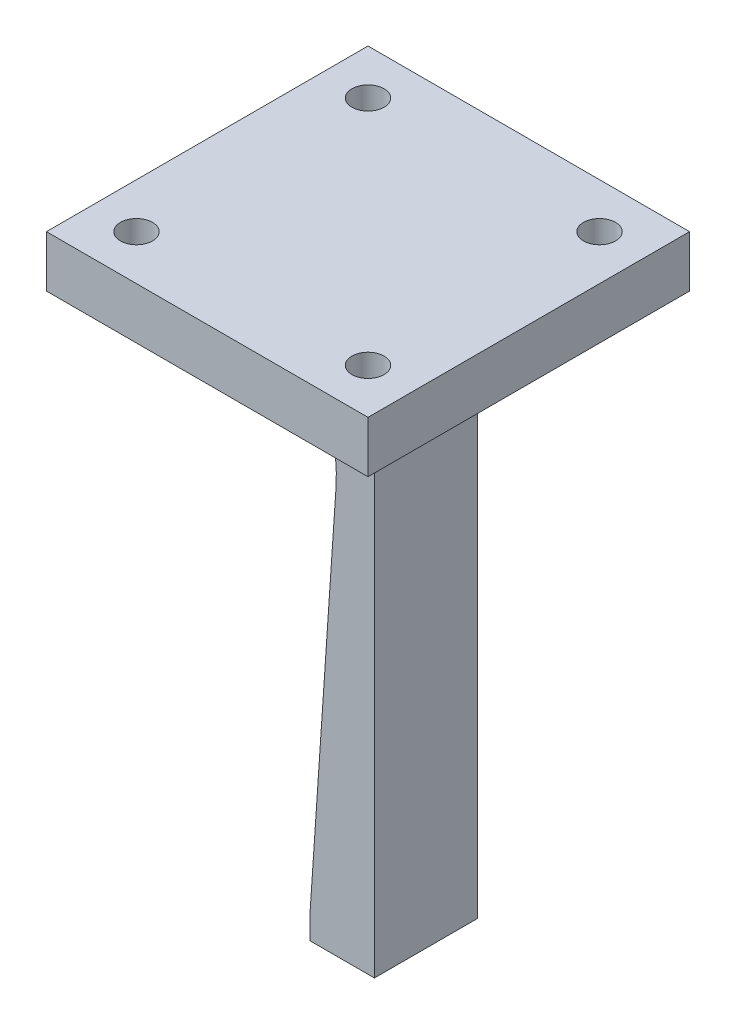
SolidWorks part; units mm, degrees
material "PBT Общее назначение"
ref_plane "Спереди" through (0, 0, 0) normal (0, 0, 1) x (1, 0, 0)
ref_plane "Сверху" through (0, 0, 0) normal (0, 1, 0) x (1, 0, 0)
ref_plane "Справа" through (0, 0, 0) normal (1, 0, 0) x (0, 0, -1)
sketch "Эскиз1" plane through (0, 0, 0) normal (0, 1, 0) x (1, 0, 0)
  line L0 (0, 0) -> (13, 0)
  line L1 (0, 0) -> (0, 13)
  line L2 (13, 0) -> (13, 13)
  line L3 (0, 13) -> (13, 13)
  line L4 (-6, 19) -> (19, 19)
  line L5 (-6, 19) -> (-6, -6)
  line L6 (19, 19) -> (19, -6)
  line L7 (-6, -6) -> (19, -6)
  line L8 (6.5, 19) -> (6.5, -6) construction
  line L9 (19, 6.5) -> (-6, 6.5) construction
  line L10 (6.5, 13) -> (6.5, 0) construction
  line L11 (13, 6.5) -> (0, 6.5) construction
  dimension "D1" = 13
  dimension "D2" = 13
  dimension "D3" = 25
  dimension "D4" = 25
extrude "Бобышка-Вытянуть1" add sketch "Эскиз1" along normal blind 4
sketch "Эскиз5" plane through (0, 4, 0) normal (0, 1, 0) x (1, 0, 0)
  line L0 (19, 6.5) -> (-6, 6.5) construction
  line L1 (19, -6) -> (19, 19) construction
  line L2 (-6, 19) -> (-6, -6) construction
ref_plane "Плоскость1" through (0, 0, -6.5) normal (0, 0, -1) x (-1, 0, 0)
sketch "Эскиз6" plane through (0, 0, -6.5) normal (0, 0, -1) x (-1, 0, 0)
  line L0 (-13, 4) -> (-13, 0) construction
  line L1 (-13, 4) -> (-13, 0) construction
  line L2 (-13, 4) -> (-9, 4)
  line L3 (-9, 4) -> (-9, -40)
  line L4 (-9, -40) -> (-6, -40)
  line L5 (-6, -40) -> (-6, -42)
  line L6 (-6, -42) -> (-11, -42)
  line L7 (-11, -42) -> (-11, 2)
  line L8 (-11, 2) -> (-13, 2)
  line L9 (-13, 2) -> (-13, 4)
  dimension "D1" = 2
  dimension "D2" = 2
  dimension "D3" = 2
  dimension "D4" = 5
  dimension "D5" = 42
  dimension "D6" = 2
extrude "Бобышка-Вытянуть5" add sketch "Эскиз6" along normal blind 4 and the other way blind 4
sketch "Эскиз7" plane through (0, 0, -10.5) normal (0, 0, -1) x (-1, 0, 0)
  line L0 (-9, -40) -> (-9, 4) construction
  line L1 (-6, -40) -> (-9, -40) construction
  line L2 (-9, -40) -> (-9, 4)
  line L3 (-6, -40) -> (-9, -40)
  line L4 (-6, -40) -> (-9, 4)
extrude "Бобышка-Вытянуть6" add sketch "Эскиз7" against normal up to surface (8 mm away) up to face at (9.75, -19, -2.5)
sketch "Эскиз9" plane through (0, 0, -2.5) normal (0, 0, 1) x (1, 0, 0)
  line L0 (9, 4) -> (0, 4)
  line L1 (0, 4) -> (0, 2)
  line L2 (6, -40) -> (9, 4) construction
  line L3 (8.0095, -10.527) -> (9, 4)
  arc A0 (8.0095, -10.527) -> (0, 2) centre (-4.4615, -9.6767) ccw
  dimension "D2" = 25
  dimension "D1" = 2
extrude "Бобышка-Вытянуть7" add sketch "Эскиз9" against normal blind 8
sketch "Эскиз10" plane through (0, 4, 0) normal (0, 1, 0) x (1, 0, 0)
  line L0 (0, 13) -> (13, 13)
  line L1 (0, 13) -> (0, -0.0017)
  line L2 (13, 13) -> (13, -0.0017)
  line L3 (0, -0.0017) -> (13, -0.0017)
extrude "Бобышка-Вытянуть8" add sketch "Эскиз10" against normal blind 2
sketch "Эскиз11" plane through (0, 4, 0) normal (0, 1, 0) x (1, 0, 0)
  line L0 (-2.5, 15.5) -> (15.5, 15.5) construction
  line L1 (-2.5, 15.5) -> (-2.5, -2.5) construction
  line L2 (15.5, 15.5) -> (15.5, -2.5) construction
  line L3 (-2.5, -2.5) -> (15.5, -2.5) construction
  line L4 (6.5, 19) -> (6.5, -6) construction
  line L5 (19, 19) -> (-6, 19) construction
  line L6 (-6, -6) -> (19, -6) construction
  line L7 (19, 6.5) -> (-6, 6.5) construction
  circle A0 centre (-2.5, 15.5) radius 1.25
  circle A1 centre (15.5, 15.5) radius 1.25
  circle A2 centre (-2.5, -2.5) radius 1.25
  circle A3 centre (15.5, -2.5) radius 1.25
  point P14 (6.5, 15.5)
  point P15 (-2.5, 6.5)
  dimension "D3" = 2.5
  dimension "D2" = 18
extrude "Вырез-Вытянуть1" cut sketch "Эскиз11" against normal through all
